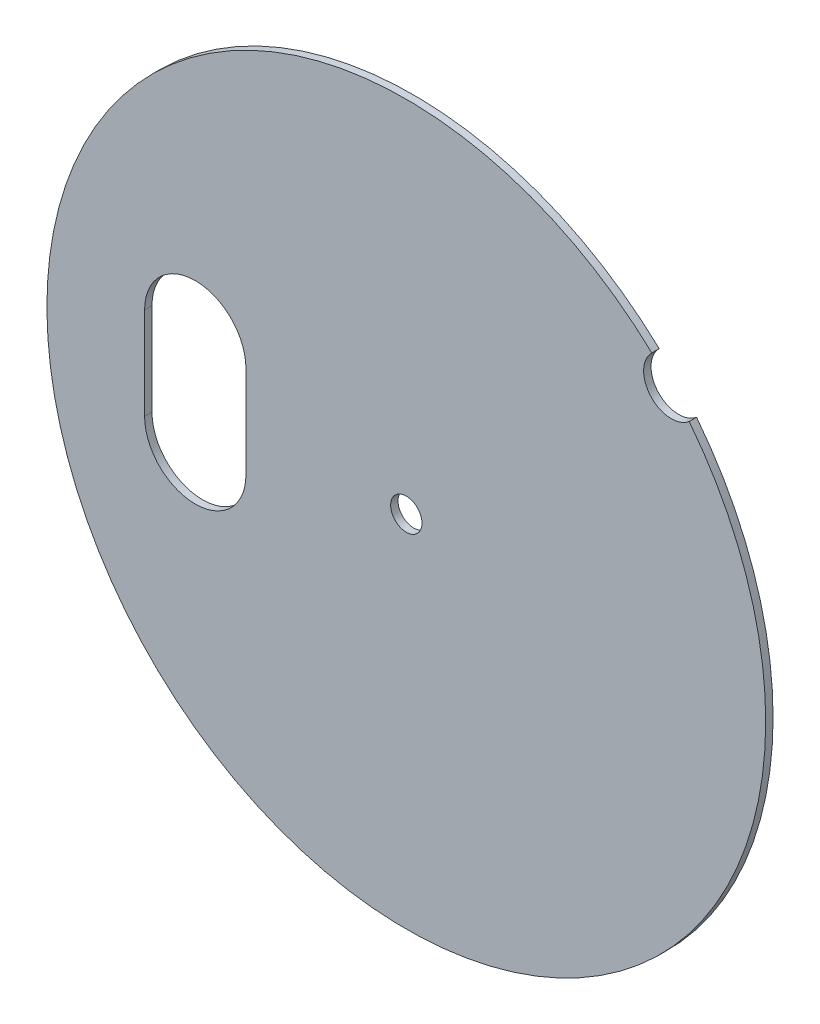
SolidWorks part; units mm, degrees
ref_plane "Plan de face" through (0, 0, 0) normal (0, 0, 1) x (1, 0, 0)
ref_plane "Plan de dessus" through (0, 0, 0) normal (0, 1, 0) x (1, 0, 0)
ref_plane "Plan de droite" through (0, 0, 0) normal (1, 0, 0) x (0, 0, -1)
sketch "Esquisse1" plane through (0, 0, 0) normal (0, 0, 1) x (1, 0, 0)
  line L0 (0, 0) -> (19.5, 0) construction
  line L1 (0, 19.5) -> (0, 0) construction
  line L2 (-6.7, -3.3481) -> (-6.7, 3.3481) construction
  line L3 (-11.45, -2.5) -> (-11.45, 2.5) construction
  line L4 (-14.2, -2.5) -> (-14.2, 2.5)
  line L5 (-8.7, -2.5) -> (-8.7, 2.5)
  line L6 (-11.45, 0) -> (0, 0) construction
  line L7 (0, 0) -> (14.3769, 13.174) construction
  arc A0 (13.3217, 14.2401) -> (15.347, 12.0299) centre (0, 0) ccw
  circle A4 centre (0, 0) radius 0.85
  arc A5 (13.3217, 14.2401) -> (15.347, 12.0299) centre (14.3769, 13.174) ccw
  arc A6 (-14.2, -2.5) -> (-8.7, -2.5) centre (-11.45, -2.5) ccw
  arc A7 (-8.7, 2.5) -> (-14.2, 2.5) centre (-11.45, 2.5) ccw
  point P5 (8.234, -1.9)
  point P6 (-7.9, -3)
  point P10 (17.506, 8.5901)
  point P11 (-11.45, 0)
  point P20 (-11.45, 0)
  dimension "D1" = 39
  dimension "D6" = 5.5
  dimension "D8" = 42.5
  dimension "D10" = 1.7
  dimension "D7" = 5
  dimension "D9" = 1.5
  dimension "D2" = 1.9
  dimension "D3" = 3
  dimension "D4" = 7.9
  dimension "D5" = 8.234
  dimension "D11" = 2
  dimension "D13" = 19.5
extrude "Boss.-Extru.1" add sketch "Esquisse1" along normal blind 0.4
